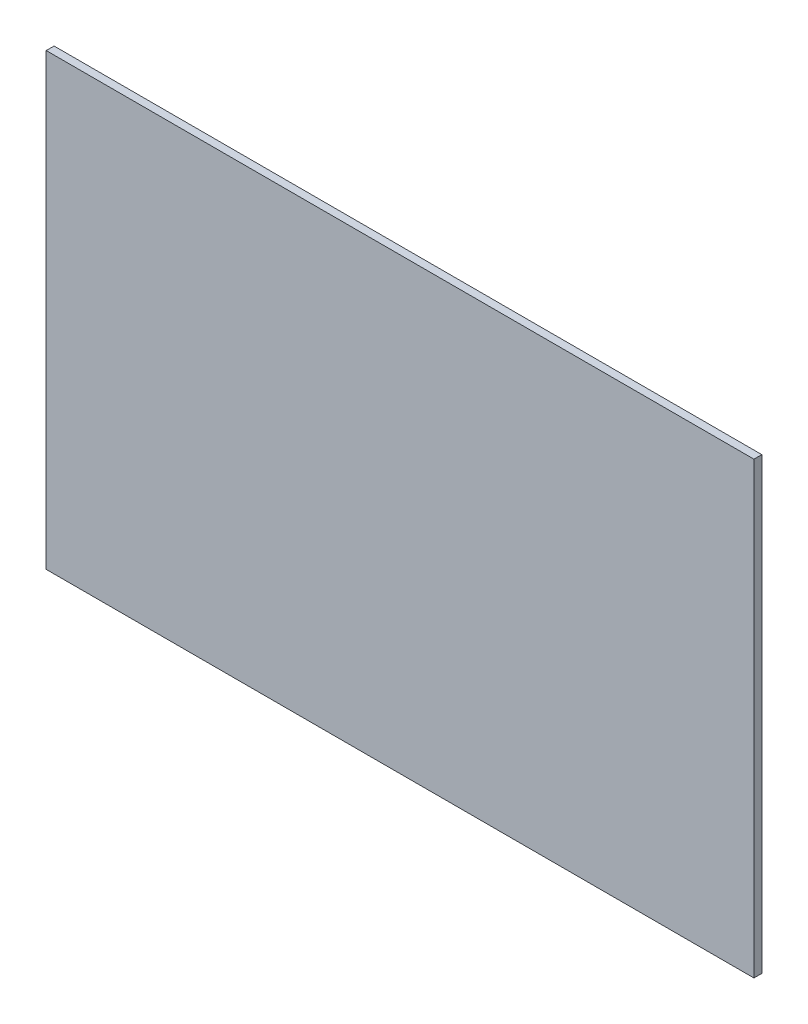
SolidWorks part; units mm, degrees
ref_plane "前视基准面" through (0, 0, 0) normal (0, 0, 1) x (1, 0, 0)
ref_plane "上视基准面" through (0, 0, 0) normal (0, 1, 0) x (1, 0, 0)
ref_plane "右视基准面" through (0, 0, 0) normal (1, 0, 0) x (0, 0, -1)
sketch "草图1" plane through (0, 0, 0) normal (0, 0, 1) x (1, 0, 0)
  line L0 (0, 0) -> (630, 0)
  line L1 (630, 0) -> (630, -400)
  line L2 (630, -400) -> (0, -400)
  line L3 (0, -400) -> (0, -18.6302)
  line L4 (0, -18.6302) -> (0, 0)
  dimension "D1" = 630
  dimension "D2" = 400
extrude "凸台-拉伸1" add sketch "草图1" along normal blind 7
sketch "草图2" plane through (0, 0, 0) normal (0, 0, -1) x (-1, 0, 0)
  line L0 (-316.8846, 0) -> (-315, -400) construction
  line L1 (-630, 0) -> (0, 0) construction
  line L2 (0, -400) -> (-630, -400) construction
  line L3 (-315, -400) -> (-315.4711, -300.0011) construction
  line L4 (-315.4711, -300.0011) -> (-245.4711, -300.0011)
  line L5 (-245.4711, -300.0011) -> (-245.4711, -250.0011)
  line L6 (-245.4711, -250.0011) -> (-245.4711, -230.0011)
  line L7 (-245.4711, -230.0011) -> (-385.4711, -230.0011)
  line L8 (-385.4711, -230.0011) -> (-385.4711, -300.0011)
  line L9 (-385.4711, -300.0011) -> (-315.4711, -300.0011)
  line L10 (-315.5722, -278.5462) -> (-330.5722, -278.5462) construction
  circle A0 centre (-315.5722, -278.5462) radius 3
  circle A1 centre (-330.5722, -278.5462) radius 0.5
  dimension "D6" = 6
  dimension "D8" = 1
  dimension "D1" = 100
  dimension "D2" = 70
  dimension "D3" = 50
  dimension "D4" = 20
  dimension "D5" = 140
  dimension "D7" = 15
extrude "凸台-拉伸2" add sketch "草图2" along normal blind 7
